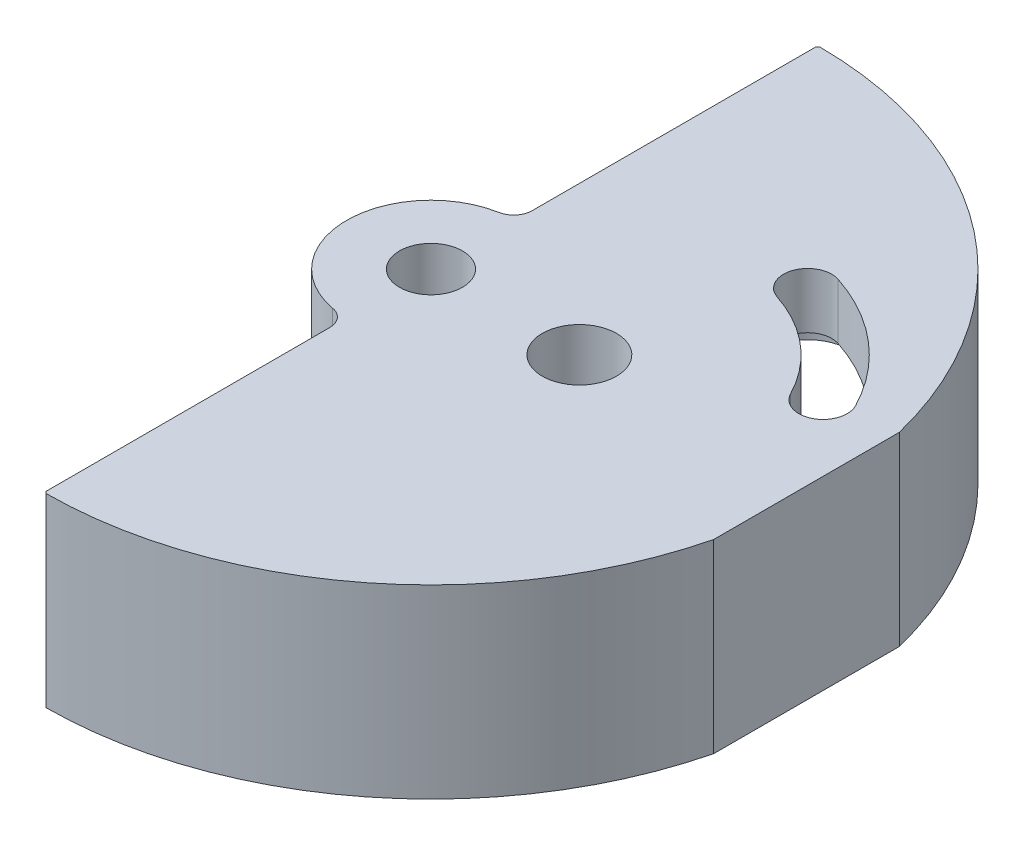
SolidWorks part; units mm, degrees
ref_plane "Front Plane" through (0, 0, 0) normal (0, 0, 1) x (1, 0, 0)
ref_plane "Top Plane" through (0, 0, 0) normal (0, 1, 0) x (1, 0, 0)
ref_plane "Right Plane" through (0, 0, 0) normal (1, 0, 0) x (0, 0, -1)
other "Configuration Table"
sketch "草图1" plane through (0, 0, 0) normal (0, 1, 0) x (1, 0, 0)
  line L0 (0, 41.7) -> (0, 10.9183)
  line L1 (0, -10.9183) -> (0, -41.7)
  arc A0 (0, -41.7) -> (0, 41.7) centre (0, 0) ccw
  circle A1 centre (0, 0) radius 6
  arc A2 (-1.6396, 8.9511) -> (-1.6396, -8.9511) centre (0, 0) ccw
  arc A3 (0, -10.9183) -> (-1.6396, -8.9511) centre (-2, -10.9183) ccw
  arc A4 (0, 10.9183) -> (-1.6396, 8.9511) centre (-2, 10.9183) cw
  dimension "D1" = 2
  dimension "D2" = 12
extrude "凸台-拉伸1" add sketch "草图1" along normal blind 20
sketch "草图2" plane through (0, 0, 0) normal (0, -1, 0) x (1, 0, 0)
  circle A0 centre (0, 0) radius 6.1
extrude "凸台-拉伸2" add sketch "草图2" against normal blind 11
sketch "草图3" plane through (0, 11, 0) normal (0, 1, 0) x (1, 0, 0)
  circle A0 centre (0, 0) radius 3.4
  dimension "D1" = 6.8
extrude "切除-拉伸1" cut sketch "草图3" against normal through all
sketch "草图4" plane through (0, 0, 0) normal (-1, 0, 0) x (0, 0, 1)
  line L0 (26.3092, 20) -> (41.7, 10) construction
  line L1 (10.9183, 20) -> (41.7, 20) construction
  line L2 (41.7, 20) -> (41.7, 0) construction
  line L3 (41.7, 10) -> (10.9183, 10) construction
  line L4 (10.9183, 20) -> (10.9183, 0) construction
  line L5 (0, 0) -> (0, 20) construction
  line L6 (8.9511, 20) -> (-8.9511, 20) construction
  circle A0 centre (33.6671, 15) radius 2.1
  circle A1 centre (20.9183, 10) radius 2.1
  circle A2 centre (-33.6671, 15) radius 2.1
  circle A3 centre (-20.9183, 10) radius 2.1
  dimension "D1" = 10
extrude "切除-拉伸2" cut sketch "草图4" against normal blind 10
mirror "镜向1" about plane through (0, 0, 0) normal (0, 1, 0) of bodies 105
delete or keep bodies "实体-删除/保留 1" type delete bodies bodies 105
sketch "草图5" plane through (0, 0, 0) normal (0, 1, 0) x (1, 0, 0)
  line L0 (0, 0) -> (40.4832, 0) construction
  line L1 (40.4832, -10) -> (40.4832, 10)
  circle A0 centre (0, 0) radius 41.7
  point P7 (40.4832, 0)
  arc M5 (0, -41.7) -> (0, 41.7) centre (0, 0) ccw
extrude "切除-拉伸3" cut sketch "草图5" against normal through all contours L1 M5
sketch "草图6" plane through (0, -20, 0) normal (0, -1, 0) x (1, 0, 0)
  line L0 (0, 0) -> (6, 0) construction
  line L5 (6, -36.1248) -> (6, -6.8418)
  line L6 (6, 6.8418) -> (6, 36.1248)
  arc A5 (6, -6.8418) -> (6, 6.8418) centre (0, 0) ccw
  arc A6 (8.4324, -38.0775) -> (8.4324, 38.0775) centre (0, 0) ccw
  arc A7 (6, -36.1248) -> (8.4324, -38.0775) centre (8, -36.1248) ccw
  arc A8 (8.4324, 38.0775) -> (6, 36.1248) centre (8, 36.1248) ccw
  point P8 (6, 0)
  dimension "D1" = 2
extrude "切除-拉伸4" cut sketch "草图6" against normal blind 12 contours A8 L6 A5 L5 A7 A6
sketch "草图7" plane through (0, -8, 0) normal (0, -1, 0) x (1, 0, 0)
  line L0 (0, 0) -> (16, 0) construction
  circle A0 centre (16, 0) radius 6.5
  dimension "D1" = 13
  dimension "D2" = 16
extrude "切除-拉伸5" cut sketch "草图7" against normal blind 1 contours A0
sketch "草图8" plane through (0, -7, 0) normal (0, -1, 0) x (1, 0, 0)
  circle A0 centre (16, 0) radius 4
  dimension "D1" = 8
extrude "切除-拉伸6" cut sketch "草图8" against normal through all
sketch "草图9" plane through (0, -8, 0) normal (0, -1, 0) x (1, 0, 0)
  line L0 (0, 0) -> (35.5, 0) construction
  line L1 (0, 0) -> (33.3341, -8.9319) construction
  line L2 (0, 0) -> (22.0805, -18.5277) construction
  line L3 (0, -41.7) -> (0, -10.9183) construction
  circle A0 centre (16, 0) radius 19.5 construction
  arc A1 (33.3341, -8.9319) -> (22.0805, -18.5277) centre (16, 0) cw construction
  arc A2 (22.8912, -20.9981) -> (35.6453, -10.1228) centre (16, 0) ccw
  arc A3 (21.2698, -16.0574) -> (31.0229, -7.7409) centre (16, 0) ccw
  arc A4 (21.2698, -16.0574) -> (22.8912, -20.9981) centre (22.0805, -18.5277) ccw
  arc A5 (35.6453, -10.1228) -> (31.0229, -7.7409) centre (33.3341, -8.9319) ccw
  point P10 (0, 0)
  point P12 (28.6523, -14.8381)
  dimension "D1" = 15
  dimension "D3" = 39
  dimension "50" = 50
extrude "切除-拉伸7" cut sketch "草图9" against normal through all contours A2 A5 A3 A4
sketch "草图10" plane through (0, -8, 0) normal (0, -1, 0) x (1, 0, 0)
  arc A0 (33.3341, -8.9319) -> (22.0805, -18.5277) centre (13.9194, 2.44) cw construction
  arc A1 (23.7127, -22.7213) -> (37.2171, -11.2062) centre (13.9194, 2.44) ccw
  arc A2 (20.4483, -14.3342) -> (29.4512, -6.6575) centre (13.9194, 2.44) ccw
  arc A3 (20.4483, -14.3342) -> (23.7127, -22.7213) centre (22.0805, -18.5277) ccw
  arc A4 (37.2171, -11.2062) -> (29.4512, -6.6575) centre (33.3341, -8.9319) ccw
  point P3 (28.5183, -14.6808)
extrude "切除-拉伸8" cut sketch "草图10" against normal blind 2
chamfer "倒角1" distance 0.2 angle 45 2 edges at (0, -10, -41.7) (0, -10, 41.7)
